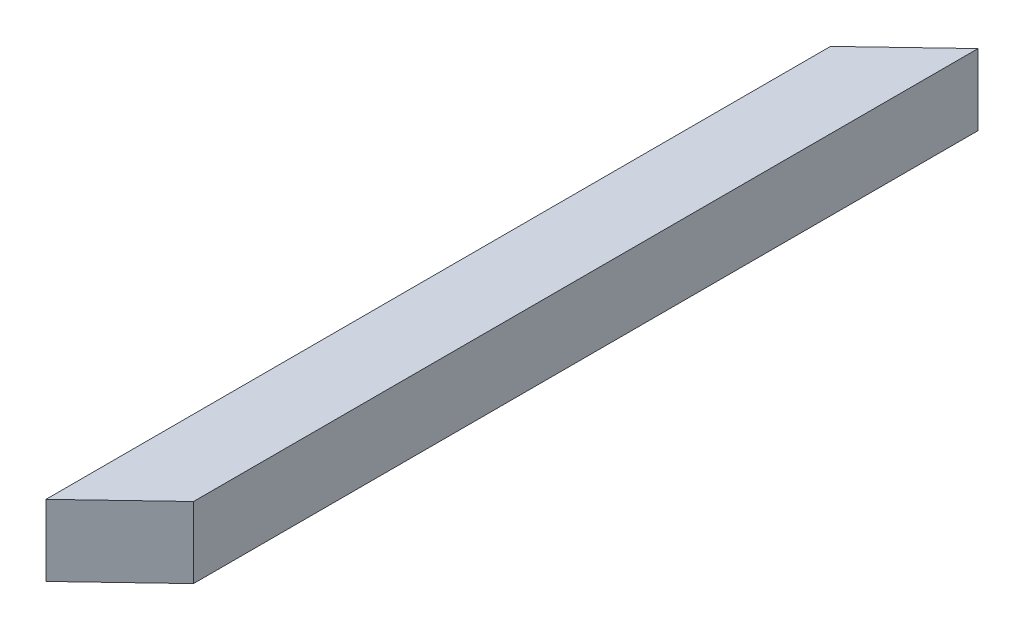
SolidWorks part; units mm, degrees
ref_plane "Front Plane" through (0, 0, 0) normal (0, 0, 1) x (1, 0, 0)
ref_plane "Top Plane" through (0, 0, 0) normal (0, 1, 0) x (1, 0, 0)
ref_plane "Right Plane" through (0, 0, 0) normal (1, 0, 0) x (0, 0, -1)
sketch "Sketch1" plane through (0, 0, 0) normal (0, 0, 1) x (1, 0, 0)
  line L1 (-29.8739, 25.9887) -> (20.1261, 25.9887)
  line L2 (-29.8739, 25.9887) -> (-29.8739, -21.0113)
  line L3 (-29.8739, -21.0113) -> (20.1261, -21.0113)
  line L4 (20.1261, 25.9887) -> (20.1261, -21.0113)
  dimension "D1" = 50
  dimension "D2" = 47
extrude "Boss-Extrude1" add sketch "Sketch1" along normal blind 566
sketch "Sketch3" plane through (0, -21.0113, 0) normal (0, -1, 0) x (1, 0, 0)
  line L0 (-29.8739, 566) -> (20.1261, 518.5135)
  line L1 (20.1261, 566) -> (20.1261, 0) construction
  line L2 (-29.8776, 565.9961) -> (279.0363, 272.6564) construction
  line L3 (20.1261, 518.5135) -> (20.1261, 566)
  line L4 (20.1261, 566) -> (-29.8739, 566)
  line L5 (-29.8739, 0) -> (20.1261, 0)
  line L6 (20.1261, 0) -> (-29.8739, 47.4792)
  line L7 (-29.8739, 566) -> (-29.8739, 0) construction
  line L8 (-288.7878, 293.3398) -> (20.1261, 0) construction
  line L9 (-29.8739, 47.4792) -> (-29.8739, 0)
extrude "Cut-Extrude1" cut sketch "Sketch3" against normal blind 50
